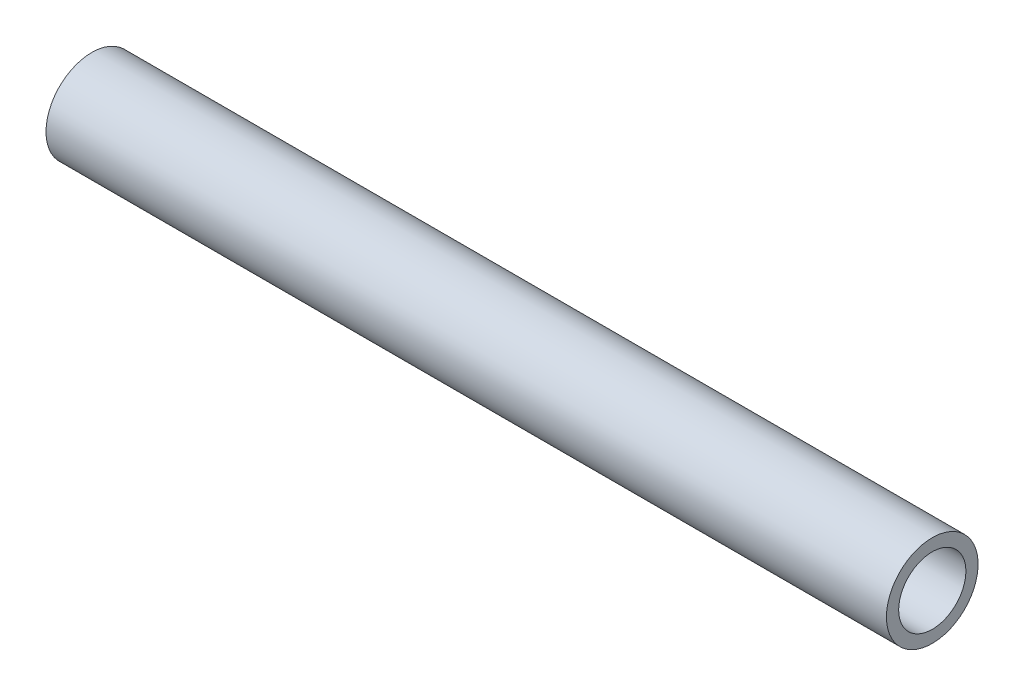
SolidWorks part; units mm, degrees
ref_plane "Front Plane" through (0, 0, 0) normal (0, 0, 1) x (1, 0, 0)
ref_plane "Top Plane" through (0, 0, 0) normal (0, 1, 0) x (1, 0, 0)
ref_plane "Right Plane" through (0, 0, 0) normal (1, 0, 0) x (0, 0, -1)
sketch "Axial profile (mm)" plane through (0, 0, 0) normal (0, 0, 1) x (1, 0, 0)
  line L0 (-110, 0) -> (75, 0) construction
  line L1 (0, 1.65) -> (41.2667, 1.65)
  line L2 (41.2667, 1.65) -> (41.2667, 2.25)
  line L3 (41.2667, 2.25) -> (0, 2.25)
  line L4 (0, 2.25) -> (0, 1.65)
revolve "Full revolution" add sketch "Axial profile (mm)" angle 360 about L0
